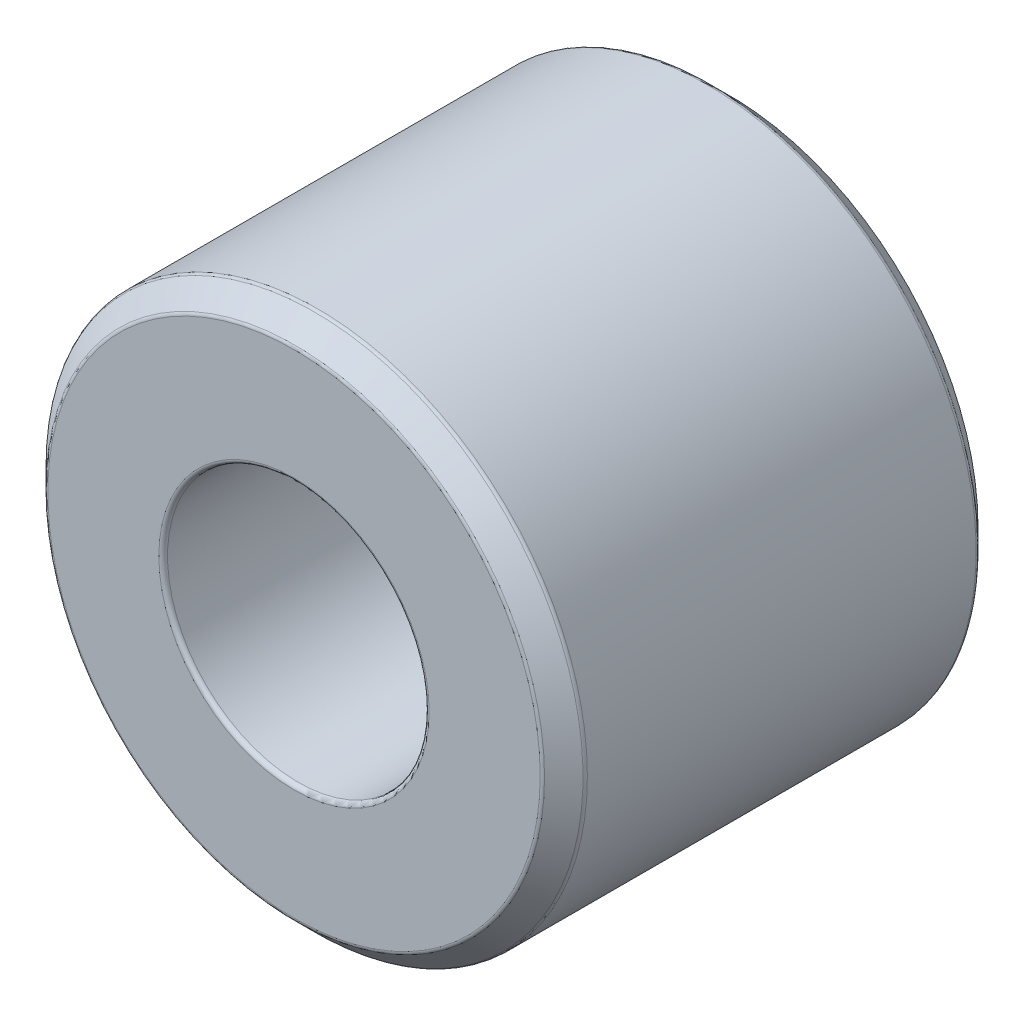
SolidWorks part; units mm, degrees
material "moto_grey"
ref_plane "Front Plane" through (0, 0, 0) normal (0, 0, 1) x (1, 0, 0)
ref_plane "Top Plane" through (0, 0, 0) normal (0, 1, 0) x (1, 0, 0)
ref_plane "Right Plane" through (0, 0, 0) normal (1, 0, 0) x (0, 0, -1)
sketch "Sketch1" plane through (0, 0, 0) normal (0, 0, 1) x (1, 0, 0)
  circle A0 centre (0, 0) radius 6.1877
  circle A1 centre (0, 0) radius 3
  dimension "D1" = 6
extrude "Boss-Extrude1" add sketch "Sketch1" along normal blind 10
fillet "Fillet1" radius 0.1 2 edges at (3, 0, 10) (3, 0, 0)
chamfer "Chamfer1" distance 0.5 angle 45 2 edges at (6.1877, 0, 0) (6.1877, 0, 10)
fillet "Fillet3" radius 0.1 4 edges at (6.1877, 0, 0.5) (5.6877, 0, 0) (6.1877, 0, 9.5) (5.6877, 0, 10)
